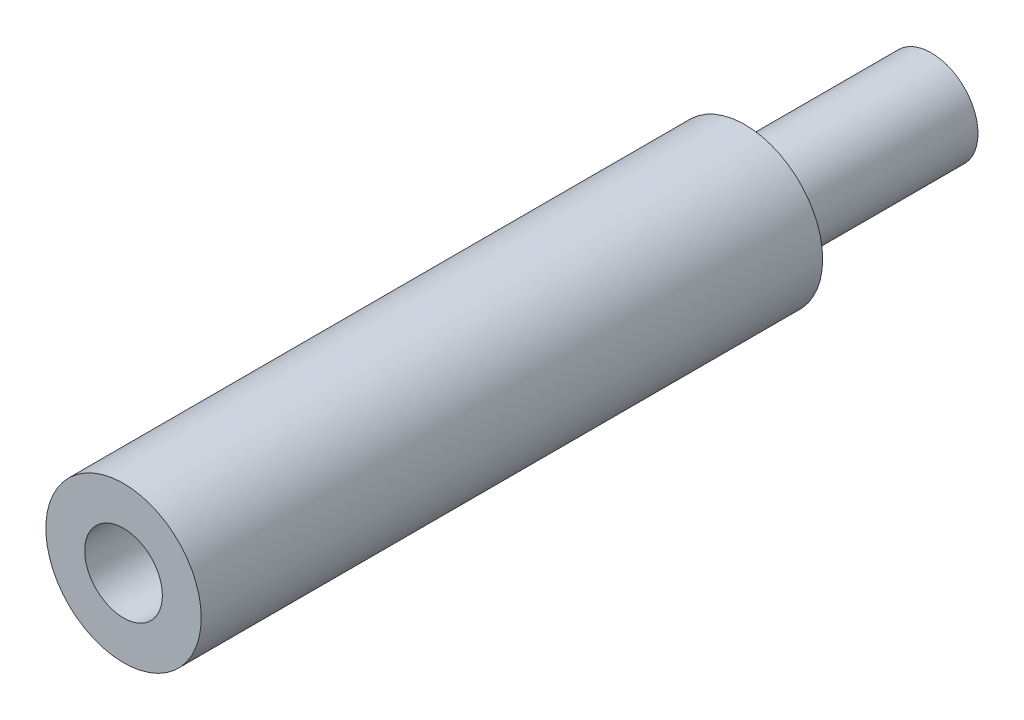
SolidWorks part; units mm, degrees
ref_plane "Front Plane" through (0, 0, 0) normal (0, 0, 1) x (1, 0, 0)
ref_plane "Top Plane" through (0, 0, 0) normal (0, 1, 0) x (1, 0, 0)
ref_plane "Right Plane" through (0, 0, 0) normal (1, 0, 0) x (0, 0, -1)
sketch "Sketch1" plane through (0, 0, 0) normal (0, 0, 1) x (1, 0, 0)
  circle A0 centre (0, 0) radius 1.5
  dimension "D1" = 3
extrude "Boss-Extrude1" add sketch "Sketch1" along normal blind 6
sketch "Sketch2" plane through (0, 0, 6) normal (0, 0, 1) x (1, 0, 0)
  circle A0 centre (0, 0) radius 2.5
  dimension "D1" = 5
extrude "Boss-Extrude2" add sketch "Sketch2" along normal blind 20
sketch "Sketch3" plane through (0, 0, 26) normal (0, 0, 1) x (1, 0, 0)
  circle A0 centre (0, 0) radius 1.25
  dimension "D1" = 2.5
extrude "Cut-Extrude1" cut sketch "Sketch3" against normal blind 6
